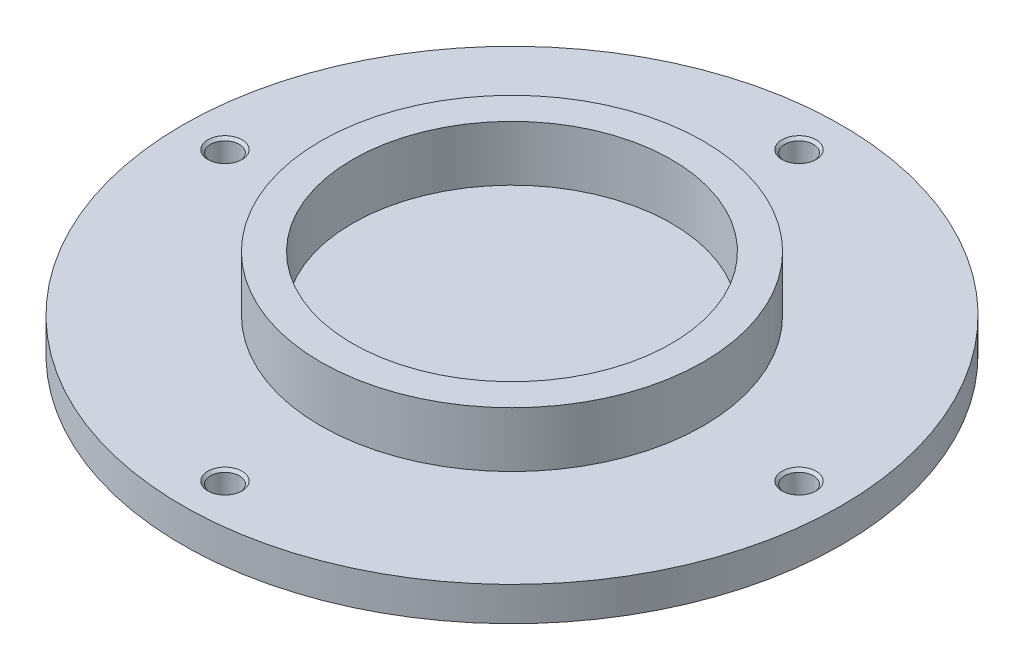
SolidWorks part; units mm, degrees
ref_plane "前视基准面" through (0, 0, 0) normal (0, 0, 1) x (1, 0, 0)
ref_plane "上视基准面" through (0, 0, 0) normal (0, 1, 0) x (1, 0, 0)
ref_plane "右视基准面" through (0, 0, 0) normal (1, 0, 0) x (0, 0, -1)
other "Configuration Table"
sketch "草图1" plane through (0, 0, 0) normal (0, 0, 1) x (1, 0, 0)
  line L0 (0, 34.8163) -> (0, -25.9388) construction
  line L1 (0, 0) -> (77.5, 0)
  line L2 (77.5, 0) -> (77.5, 8)
  line L3 (77.5, 8) -> (45, 8)
  line L4 (45, 8) -> (45, 21)
  line L5 (45, 21) -> (37.5, 21)
  line L6 (37.5, 21) -> (37.5, 8)
  line L7 (37.5, 8) -> (0, 8)
  line L8 (0, 8) -> (0, 0)
  dimension "D1" = 77.5
  dimension "D2" = 8
  dimension "D3" = 7.5
  dimension "D4" = 37.5
  dimension "D5" = 13
revolve "旋转1" add sketch "草图1" angle 360 about L8
sketch "草图2" plane through (0, 0, 0) normal (0, 1, 0) x (1, 0, 0)
  circle A0 centre (0, 0) radius 67.5
  circle A1 centre (67.5, 0) radius 4.5
  circle A2 centre (0, -67.5) radius 4.5
  circle A3 centre (-67.5, 0) radius 4.5
  circle A4 centre (0, 67.5) radius 4.5
  point P14 (0, 0)
  dimension "D1" = 4
  dimension "D2" = 135
hole_wizard "M8 螺纹孔1" positions "草图7" profile "草图8" tap size "M8" standard "GB" end condition through all
sketch "草图7" plane through (0, 8, 0) normal (0, 1, 0) x (1, 0, 0)
  point P0 (-67.5, 0)
  point P3 (67.5, 0)
  point P6 (0, -67.5)
  point P9 (0, 67.5)
sketch "草图8" plane through (-67.5, 8, 0) normal (1, 0, 0) x (0, 0, 1)
  line L0 (0, 0) -> (0, 8)
  line L1 (0, 8) -> (3.4, 8)
  line L2 (3.4, 8) -> (3.4, 0.625)
  line L3 (3.4, 0.625) -> (4.025, 0)
  line L5 (4.025, 0) -> (0, 0)
  line L6 (-3.4, 0.625) -> (-4.025, 0) construction
  line L11 (0, -6.35) -> (0, 107.95) construction
  dimension "通孔螺纹孔钻头直径" = 6.8
  dimension "通孔螺纹孔钻头深度" = 8
  dimension "近端锥形沉头孔直径" = 8.05
  dimension "近端锥形沉头孔角度" = 90
cosmetic thread "孔螺蚊线1" parameters "D2"=8
cosmetic thread "孔螺蚊线2" parameters "D2"=8
cosmetic thread "孔螺蚊线3" parameters "D2"=8
cosmetic thread "孔螺蚊线4" parameters "D2"=8
